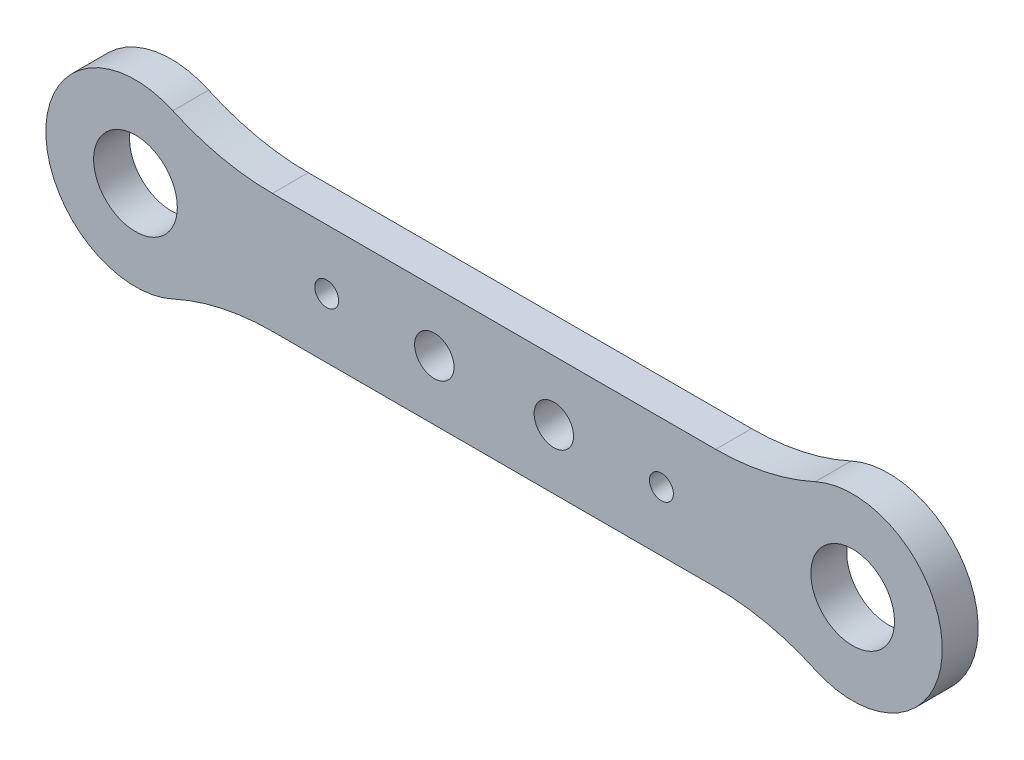
SolidWorks part; units mm, degrees
ref_plane "Plano frontal" through (0, 0, 0) normal (0, 0, 1) x (1, 0, 0)
ref_plane "Plano superior" through (0, 0, 0) normal (0, 1, 0) x (1, 0, 0)
ref_plane "Plano direito" through (0, 0, 0) normal (1, 0, 0) x (0, 0, -1)
sketch "Esboço1" plane through (0, 0, 0) normal (0, 0, 1) x (1, 0, 0)
  line L0 (5.5902, -5) -> (54.4098, -5)
  line L1 (0, 0) -> (60, 0) construction
  line L2 (5.5902, 5) -> (54.4098, 5)
  line L3 (0, 5) -> (80, 5) construction
  line L4 (0, -5) -> (80, -5) construction
  line L5 (30, 5) -> (30, -5) construction
  line L7 (0, 0) -> (80, 0) construction
  circle A0 centre (44, 0) radius 1
  circle A1 centre (16, 0) radius 1
  arc A3 (5.5902, 5) -> (5.5902, -5) centre (0, 0) ccw
  circle A13 centre (0, 0) radius 3.5
  arc A22 (54.4098, 5) -> (54.4098, -5) centre (60, 0) cw
  circle A25 centre (60, 0) radius 3.5
  circle A26 centre (25, 0) radius 1.65
  circle A27 centre (35, 0) radius 1.65
  point P14 (30, 0)
  point P32 (0, 0)
  dimension "D3" = 2
  dimension "D4" = 16
  dimension "D6" = 7
  dimension "D8" = 15
  dimension "D9" = 3.3
  dimension "D2" = 5
  dimension "D5" = 5
  dimension "D7" = 30
  dimension "D10" = 10
extrude "Ressalto-extrusão1" add sketch "Esboço1" along normal blind 3
fillet "Filete1" radius 20 4 edges at (5.5902, -5, 1.5) (54.4098, -5, 1.5) (54.4098, 5, 1.5) (5.5902, 5, 1.5)
